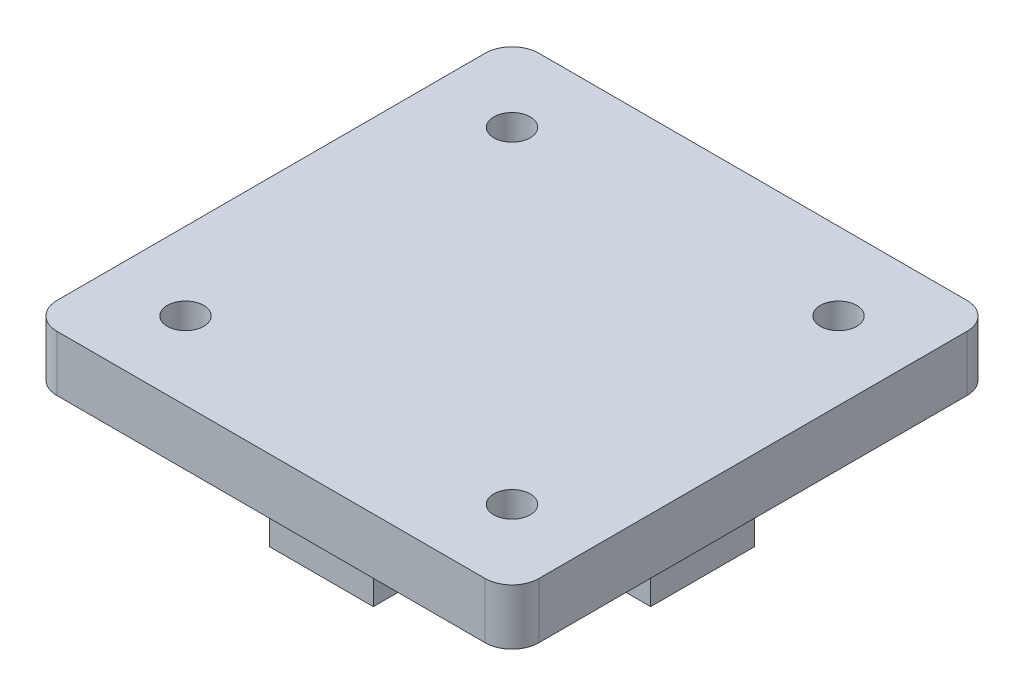
SolidWorks part; units mm, degrees
ref_plane "Front Plane" through (0, 0, 0) normal (0, 0, 1) x (1, 0, 0)
ref_plane "Top Plane" through (0, 0, 0) normal (0, 1, 0) x (1, 0, 0)
ref_plane "Right Plane" through (0, 0, 0) normal (1, 0, 0) x (0, 0, -1)
sketch "Sketch1" plane through (0, 0, 0) normal (0, 1, 0) x (1, 0, 0)
  line L1 (-22.5, 22.5) -> (22.5, 22.5)
  line L2 (-22.5, 22.5) -> (-22.5, -22.5)
  line L3 (-22.5, -22.5) -> (22.5, -22.5)
  line L4 (22.5, 22.5) -> (22.5, -22.5)
  line L5 (-22.5, 22.5) -> (22.5, -22.5) construction
  line L6 (-22.5, -22.5) -> (22.5, 22.5) construction
  point P0 (0, 0)
  dimension "D1" = 45
  dimension "D2" = 45
extrude "Boss-Extrude1" add sketch "Sketch1" against normal blind 5.2
sketch "Sketch2" plane through (0, -5.2, 0) normal (0, -1, 0) x (1, 0, 0)
  line L0 (-4.85, 12) -> (-4.85, 17.8)
  line L1 (-12, -4.85) -> (-17.8, -4.85)
  line L2 (-12, -4.85) -> (-12, 4.85)
  line L3 (-12, 4.85) -> (-17.8, 4.85)
  line L4 (-17.8, -4.85) -> (-17.8, 4.85)
  line L5 (-12, -4.85) -> (-17.8, 4.85) construction
  line L6 (-12, 4.85) -> (-17.8, -4.85) construction
  line L7 (-4.85, 12) -> (4.85, 12)
  line L8 (4.85, 12) -> (4.85, 17.8)
  line L9 (-4.85, 17.8) -> (4.85, 17.8)
  line L10 (-4.85, 12) -> (4.85, 17.8) construction
  line L11 (4.85, 12) -> (-4.85, 17.8) construction
  line L12 (12, 4.85) -> (17.8, 4.85)
  line L13 (12, 4.85) -> (12, -4.85)
  line L14 (12, -4.85) -> (17.8, -4.85)
  line L15 (17.8, 4.85) -> (17.8, -4.85)
  line L16 (12, 4.85) -> (17.8, -4.85) construction
  line L17 (12, -4.85) -> (17.8, 4.85) construction
  line L18 (4.85, -12) -> (4.85, -17.8)
  line L19 (4.85, -12) -> (-4.85, -12)
  line L20 (-4.85, -12) -> (-4.85, -17.8)
  line L21 (4.85, -17.8) -> (-4.85, -17.8)
  line L22 (4.85, -12) -> (-4.85, -17.8) construction
  line L23 (-4.85, -12) -> (4.85, -17.8) construction
  point P0 (-14.9, 0)
  point P5 (0, 14.9)
  point P13 (14.9, 0)
  point P18 (0, -14.9)
  point P23 (0, 0)
  dimension "D1" = 5.8
  dimension "D2" = 9.7
  dimension "D3" = 12
  dimension "D4" = 4
extrude "Boss-Extrude2" add sketch "Sketch2" along normal blind 7
sketch "Sketch3" plane through (0, 0, 0) normal (0, 1, 0) x (1, 0, 0)
  line L1 (-15.25, 15.25) -> (15.25, 15.25) construction
  line L2 (-15.25, 15.25) -> (-15.25, -15.25) construction
  line L3 (-15.25, -15.25) -> (15.25, -15.25) construction
  line L4 (15.25, 15.25) -> (15.25, -15.25) construction
  line L5 (-15.25, 15.25) -> (15.25, -15.25) construction
  line L6 (-15.25, -15.25) -> (15.25, 15.25) construction
  circle A0 centre (-15.25, 15.25) radius 1.7
  circle A1 centre (15.25, 15.25) radius 1.7
  circle A2 centre (-15.25, -15.25) radius 1.7
  circle A3 centre (15.25, -15.25) radius 1.7
  point P0 (0, 0)
  dimension "D3" = 3.4
  dimension "D1" = 30.5
  dimension "D2" = 30.5
extrude "Cut-Extrude1" cut sketch "Sketch3" against normal through all both and the other way through all
sketch "Sketch4" plane through (0, -5.2, 0) normal (0, -1, 0) x (1, 0, 0)
  line L0 (12.6, 13.72) -> (15.25, 12.19)
  line L1 (-13.72, 12.6) -> (-12.19, 15.25)
  line L2 (-12.19, 15.25) -> (-13.72, 17.9)
  line L3 (-13.72, 17.9) -> (-16.78, 17.9)
  line L4 (-16.78, 17.9) -> (-18.31, 15.25)
  line L5 (-18.31, 15.25) -> (-16.78, 12.6)
  line L6 (-16.78, 12.6) -> (-13.72, 12.6)
  line L7 (15.25, 12.19) -> (17.9, 13.72)
  line L8 (17.9, 13.72) -> (17.9, 16.78)
  line L9 (17.9, 16.78) -> (15.25, 18.31)
  line L10 (15.25, 18.31) -> (12.6, 16.78)
  line L11 (12.6, 16.78) -> (12.6, 13.72)
  line L12 (13.72, -12.6) -> (12.19, -15.25)
  line L13 (12.19, -15.25) -> (13.72, -17.9)
  line L14 (13.72, -17.9) -> (16.78, -17.9)
  line L15 (16.78, -17.9) -> (18.31, -15.25)
  line L16 (18.31, -15.25) -> (16.78, -12.6)
  line L17 (16.78, -12.6) -> (13.72, -12.6)
  line L18 (-12.6, -13.72) -> (-15.25, -12.19)
  line L19 (-15.25, -12.19) -> (-17.9, -13.72)
  line L20 (-17.9, -13.72) -> (-17.9, -16.78)
  line L21 (-17.9, -16.78) -> (-15.25, -18.31)
  line L22 (-15.25, -18.31) -> (-12.6, -16.78)
  line L23 (-12.6, -16.78) -> (-12.6, -13.72)
  circle A0 centre (-15.25, 15.25) radius 2.65 construction
  point P30 (0, 0)
  dimension "D1" = 5.3
  dimension "D2" = 4
extrude "Cut-Extrude2" cut sketch "Sketch4" against normal blind 2.5
fillet "Fillet1" radius 2.5 4 edges at (-22.5, -2.6, 22.5) (22.5, -2.6, 22.5) (-22.5, -2.6, -22.5) (22.5, -2.6, -22.5)
